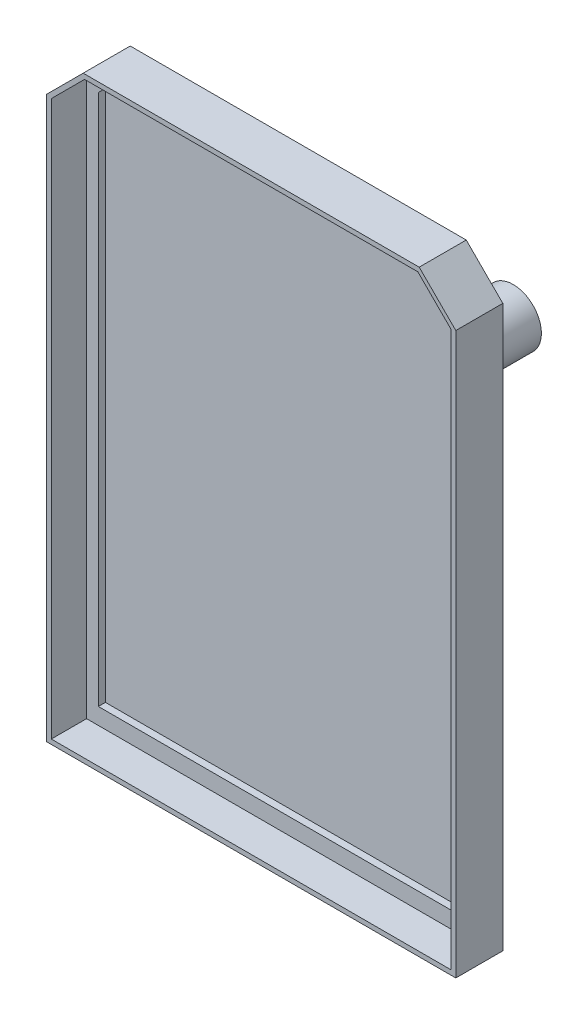
SolidWorks part; units mm, degrees
ref_plane "Front Plane" through (0, 0, 0) normal (1, 0, 0) x (0, 1, 0)
ref_plane "Top Plane" through (0, 0, 0) normal (0, 0, 1) x (0, 1, 0)
ref_plane "Right Plane" through (0, 0, 0) normal (0, 1, 0) x (-1, 0, 0)
sketch "Sketch1" plane through (0, 0, 0) normal (0, 0, 1) x (0, 1, 0)
  line L0 (54.0503, 40) -> (59, 35.0503)
  line L1 (-62.5, -42.5) -> (62.5, -42.5) construction
  line L2 (-62.5, -42.5) -> (-62.5, 42.5)
  line L3 (-62.5, 42.5) -> (62.5, 42.5) construction
  line L4 (62.5, -42.5) -> (62.5, 42.5) construction
  line L5 (-62.5, -42.5) -> (62.5, 42.5) construction
  line L6 (-62.5, 42.5) -> (62.5, -42.5) construction
  line L7 (-59, -40) -> (59, -40) construction
  line L8 (-59, -40) -> (-59, 40)
  line L9 (-59, 40) -> (59, 40) construction
  line L10 (59, -40) -> (59, 40) construction
  line L11 (-59, -40) -> (59, 40) construction
  line L12 (-59, 40) -> (59, -40) construction
  line L13 (-63.5, -43.5) -> (63.5, -43.5) construction
  line L14 (-63.5, -43.5) -> (-63.5, 43.5)
  line L15 (-63.5, 43.5) -> (63.5, 43.5) construction
  line L16 (63.5, -43.5) -> (63.5, 43.5) construction
  line L17 (-63.5, -43.5) -> (63.5, 43.5) construction
  line L18 (-63.5, 43.5) -> (63.5, -43.5) construction
  line L19 (-59, 40) -> (54.0503, 40)
  line L20 (59, 35.0503) -> (59, -40) construction
  line L21 (59, -35.0503) -> (54.0503, -40)
  line L22 (59, -35.0503) -> (59, 35.0503)
  line L23 (54.0503, -40) -> (-59, -40)
  line L24 (55.4289, 42.5) -> (62.5, 35.4289)
  line L25 (62.5, -35.4289) -> (55.4289, -42.5)
  line L26 (55.4289, -42.5) -> (-62.5, -42.5)
  line L27 (62.5, -35.4289) -> (62.5, 35.4289)
  line L28 (55.4289, 42.5) -> (-62.5, 42.5)
  line L29 (55.7218, 43.5) -> (63.5, 35.7218)
  line L30 (63.5, -35.7218) -> (55.7218, -43.5)
  line L31 (55.7218, -43.5) -> (-63.5, -43.5)
  line L32 (63.5, -35.7218) -> (63.5, 35.7218)
  line L33 (55.7218, 43.5) -> (-63.5, 43.5)
  point P0 (0, 0)
  point P5 (0, 0)
  point P11 (0, 0)
  dimension "D1" = 85
  dimension "D2" = 125
  dimension "D3" = 118
  dimension "D4" = 80
  dimension "D5" = 87
  dimension "D6" = 127
  dimension "D7" = 7
  dimension "D8" = 45
  dimension "D9" = 7
  dimension "D10" = 45
  dimension "D11" = 10
  dimension "D12" = 10
  dimension "D13" = 11
  dimension "D14" = 11
extrude "Boss-Extrude1" add sketch "Sketch1" along normal blind 1.5 contours L1 L4 L3 L2 L10 L7 L8 L9
sketch "Sketch2" plane through (0, 0, 0) normal (0, 0, 1) x (0, 1, 0)
  line L4 (55.7218, 43.5) -> (-63.5, 43.5)
  line L5 (55.7218, 43.5) -> (-63.5, 43.5)
  line L6 (63.5, 35.7218) -> (55.7218, 43.5)
  line L7 (-63.5, 43.5) -> (-63.5, -43.5)
  line L11 (-63.5, 43.5) -> (-63.5, -43.5)
  line L12 (54.0503, 40) -> (-59, 40)
  line L13 (54.0503, 40) -> (-59, 40)
  line L14 (59, 35.0503) -> (54.0503, 40)
  line L15 (-59, 40) -> (-59, -40)
  line L19 (-59, 40) -> (-59, -40) construction
  line L20 (55.4289, 42.5) -> (-62.5, 42.5)
  line L21 (55.4289, 42.5) -> (-62.5, 42.5)
  line L22 (62.5, 35.4289) -> (55.4289, 42.5)
  line L23 (-62.5, 42.5) -> (-62.5, -42.5)
  line L27 (-62.5, 42.5) -> (-62.5, -42.5)
  line L30 (59, 35.0503) -> (54.0503, 40)
  line L31 (59, -35.0503) -> (59, 35.0503)
  line L32 (59, -35.0503) -> (59, 35.0503)
  line L33 (54.0503, -40) -> (59, -35.0503)
  line L34 (54.0503, -40) -> (59, -35.0503)
  line L35 (-59, -40) -> (54.0503, -40)
  line L36 (-59, -40) -> (54.0503, -40)
  line L37 (62.5, 35.4289) -> (55.4289, 42.5)
  line L38 (62.5, -35.4289) -> (62.5, 35.4289)
  line L39 (62.5, -35.4289) -> (62.5, 35.4289)
  line L40 (55.4289, -42.5) -> (62.5, -35.4289)
  line L41 (55.4289, -42.5) -> (62.5, -35.4289)
  line L42 (-62.5, -42.5) -> (55.4289, -42.5)
  line L43 (-62.5, -42.5) -> (55.4289, -42.5)
  line L44 (63.5, 35.7218) -> (55.7218, 43.5)
  line L45 (63.5, -35.7218) -> (63.5, 35.7218)
  line L46 (63.5, -35.7218) -> (63.5, 35.7218)
  line L47 (55.7218, -43.5) -> (63.5, -35.7218)
  line L48 (55.7218, -43.5) -> (63.5, -35.7218)
  line L49 (-63.5, -43.5) -> (55.7218, -43.5)
  line L50 (-63.5, -43.5) -> (55.7218, -43.5)
  dimension "D1" = 0
  dimension "D2" = 0
  dimension "D3" = 0
extrude "Boss-Extrude2" add sketch "Sketch2" along normal blind 9 contours L11 L50 L48 L46 L44 L5 L43 L27 L21 L37 L39 L41
sketch "Sketch3" plane through (0, 0, 0) normal (0, 0, 1) x (0, 1, 0)
  line L4 (55.7218, 43.5) -> (-63.5, 43.5)
  line L5 (55.7218, 43.5) -> (-63.5, 43.5)
  line L6 (63.5, 35.7218) -> (55.7218, 43.5)
  line L7 (-63.5, 43.5) -> (-63.5, -43.5)
  line L11 (-63.5, 43.5) -> (-63.5, -43.5)
  line L12 (54.0503, 40) -> (-59, 40)
  line L13 (54.0503, 40) -> (-59, 40)
  line L14 (59, 35.0503) -> (54.0503, 40)
  line L15 (-59, 40) -> (-59, -40)
  line L19 (-59, 40) -> (-59, -40) construction
  line L20 (55.4289, 42.5) -> (-62.5, 42.5)
  line L21 (55.4289, 42.5) -> (-62.5, 42.5)
  line L22 (62.5, 35.4289) -> (55.4289, 42.5)
  line L23 (-62.5, 42.5) -> (-62.5, -42.5)
  line L27 (-62.5, 42.5) -> (-62.5, -42.5) construction
  line L30 (59, 35.0503) -> (54.0503, 40)
  line L31 (59, -35.0503) -> (59, 35.0503)
  line L32 (59, -35.0503) -> (59, 35.0503)
  line L33 (54.0503, -40) -> (59, -35.0503)
  line L34 (54.0503, -40) -> (59, -35.0503)
  line L35 (-59, -40) -> (54.0503, -40)
  line L36 (-59, -40) -> (54.0503, -40)
  line L37 (62.5, 35.4289) -> (55.4289, 42.5)
  line L38 (62.5, -35.4289) -> (62.5, 35.4289)
  line L39 (62.5, -35.4289) -> (62.5, 35.4289)
  line L40 (55.4289, -42.5) -> (62.5, -35.4289)
  line L41 (55.4289, -42.5) -> (62.5, -35.4289)
  line L42 (-62.5, -42.5) -> (55.4289, -42.5)
  line L43 (-62.5, -42.5) -> (55.4289, -42.5)
  line L44 (63.5, 35.7218) -> (55.7218, 43.5)
  line L45 (63.5, -35.7218) -> (63.5, 35.7218)
  line L46 (63.5, -35.7218) -> (63.5, 35.7218)
  line L47 (55.7218, -43.5) -> (63.5, -35.7218)
  line L48 (55.7218, -43.5) -> (63.5, -35.7218)
  line L49 (-63.5, -43.5) -> (55.7218, -43.5)
  line L50 (-63.5, -43.5) -> (55.7218, -43.5)
  dimension "D1" = 0
  dimension "D2" = 0
  dimension "D3" = 0
extrude "Boss-Extrude3" add sketch "Sketch3" against normal blind 1
sketch "Sketch4" plane through (0, 0, -1) normal (0, 0, -1) x (1, 0, 0)
  circle A0 centre (0, 0) radius 6 construction
  circle A1 centre (0, 0) radius 4.25 construction
  circle A2 centre (-4.3, -4.3) radius 4.25
  circle A3 centre (-4.3, -4.3) radius 6
  dimension "D1" = 8.5
  dimension "D2" = 12
  dimension "D4" = 12
  dimension "D5" = 8.5
  dimension "D6" = 4.3
  dimension "D7" = 4.3
  dimension "D3" = 1.75
extrude "Boss-Extrude4" add sketch "Sketch4" along normal blind 50
sketch "Sketch5" plane through (0, 0, -1) normal (0, 0, -1) x (1, 0, 0)
  circle A1 centre (-4.3, -4.3) radius 6
  circle A2 centre (-4.3, -4.3) radius 6
  circle A3 centre (-4.3, -4.3) radius 4.25
  circle A4 centre (-4.3, -4.3) radius 4.25
  dimension "D1" = 0
  dimension "D2" = 0
extrude "Boss-Extrude5" add sketch "Sketch5" along normal blind 20
fillet "Fillet1" radius 30 1 edges at (1.7, 4.3, -1)
